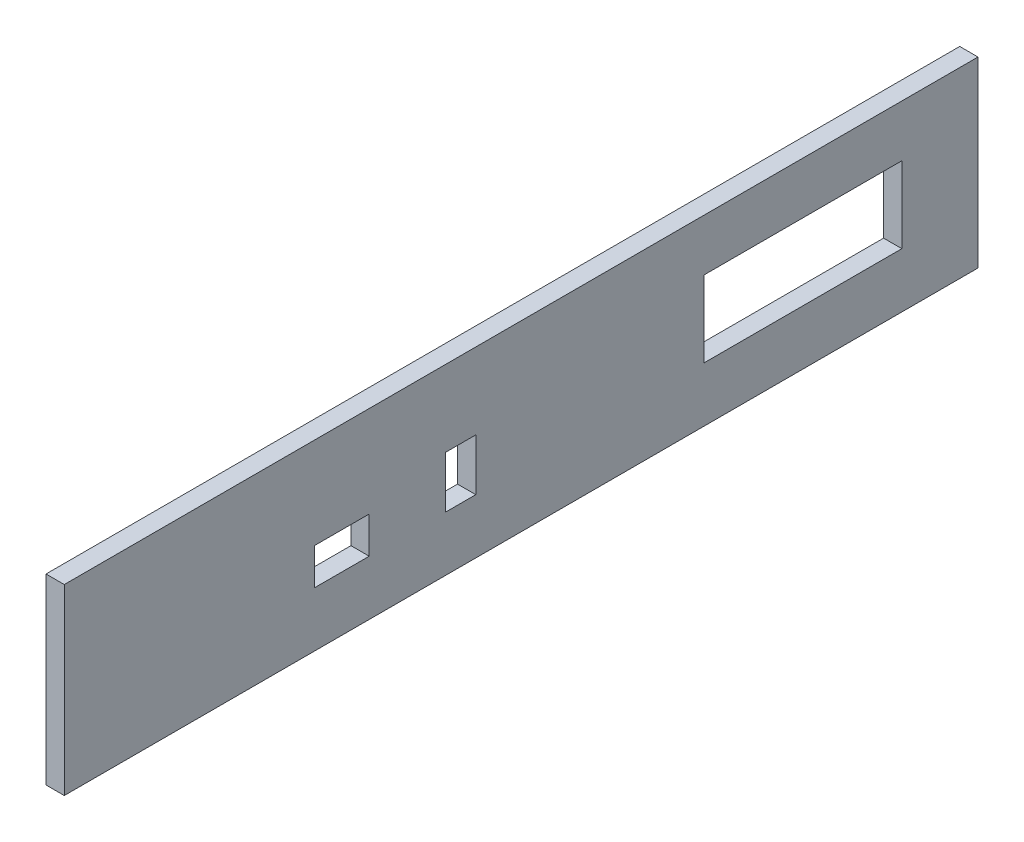
SolidWorks part; units mm, degrees
material "CA"
ref_plane "Front Plane" through (0, 0, 0) normal (0, 0, 1) x (1, 0, 0)
ref_plane "Top Plane" through (0, 0, 0) normal (0, 1, 0) x (1, 0, 0)
ref_plane "Right Plane" through (0, 0, 0) normal (1, 0, 0) x (0, 0, -1)
sketch "Sketch1" plane through (0, 0, 0) normal (1, 0, 0) x (0, 0, -1)
  line L1 (-150, 30) -> (150, 30)
  line L2 (-150, 30) -> (-150, -30)
  line L3 (-150, -30) -> (150, -30)
  line L4 (150, 30) -> (150, -30)
  line L5 (125, 13) -> (60, 13)
  line L6 (125, 13) -> (125, -12)
  line L7 (125, -12) -> (60, -12)
  line L8 (60, 13) -> (60, -12)
  line L9 (-14.8851, 5) -> (-24.8851, 5)
  line L10 (-14.8851, 5) -> (-14.8851, -12)
  line L11 (-14.8851, -12) -> (-24.8851, -12)
  line L12 (-24.8851, 5) -> (-24.8851, -12)
  line L13 (-49.8851, 0) -> (-67.8851, 0)
  line L14 (-49.8851, 0) -> (-49.8851, -12)
  line L15 (-49.8851, -12) -> (-67.8851, -12)
  line L16 (-67.8851, 0) -> (-67.8851, -12)
  point P4 (0, 30)
  point P5 (-150, 0)
  dimension "D1" = 300
  dimension "D2" = 60
  dimension "D3" = 65
  dimension "D4" = 25
  dimension "D5" = 18
  dimension "D6" = 25
  dimension "D7" = 17
  dimension "D8" = 10
  dimension "D9" = 25
  dimension "D10" = 12
  dimension "D11" = 18
  dimension "D12" = 18
extrude "Boss-Extrude1" add sketch "Sketch1" along normal blind 6
